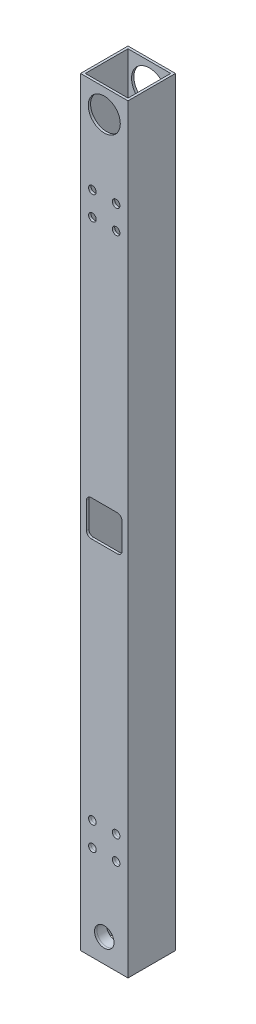
SolidWorks part; units mm, degrees
material "6061 合金"
ref_plane "前视基准面" through (0, 0, 0) normal (0, 0, 1) x (1, 0, 0)
ref_plane "上视基准面" through (0, 0, 0) normal (0, 1, 0) x (1, 0, 0)
ref_plane "右视基准面" through (0, 0, 0) normal (1, 0, 0) x (0, 0, -1)
sketch "草图1" plane through (0, 0, 0) normal (0, 1, 0) x (1, 0, 0)
  line L0 (1, 1) -> (1, 19)
  line L1 (0, 0) -> (20, 0)
  line L2 (0, 0) -> (0, 20)
  line L3 (0, 20) -> (20, 20)
  line L4 (20, 0) -> (20, 20)
  line L5 (1, 19) -> (19, 19)
  line L6 (19, 1) -> (19, 19)
  line L7 (1, 1) -> (19, 1)
  dimension "D1" = 20
  dimension "D2" = 1
extrude "凸台-拉伸1" add sketch "草图1" along normal blind 320
sketch "草图2" plane through (0, 0, -20) normal (0, 0, -1) x (-1, 0, 0)
  line L0 (-20, 160) -> (0, 160) construction
  line L1 (-20, 320) -> (-20, 0) construction
  line L3 (-5.0503, 155.0503) -> (-14.9497, 155.0503) construction
  line L4 (-5.0503, 155.0503) -> (-5.0503, 164.9497) construction
  line L5 (-5.0503, 164.9497) -> (-14.9497, 164.9497) construction
  line L6 (-14.9497, 155.0503) -> (-14.9497, 164.9497) construction
  line L7 (-5.0503, 155.0503) -> (-14.9497, 164.9497) construction
  line L8 (-5.0503, 164.9497) -> (-14.9497, 155.0503) construction
  line L9 (0, 320) -> (0, 0) construction
  circle A0 centre (-14.9497, 155.0503) radius 1.6
  circle A1 centre (-14.9497, 164.9497) radius 1.6
  circle A2 centre (-5.0503, 164.9497) radius 1.6
  circle A3 centre (-5.0503, 155.0503) radius 1.6
  point P4 (-10, 160)
  dimension "D2" = 3.2
  dimension "D1" = 14
extrude "切除-拉伸1" cut sketch "草图2" against normal through all
sketch "草图3" plane through (0, 0, 0) normal (0, 0, 1) x (1, 0, 0)
  line L0 (20, 160) -> (0, 160) construction
  line L5 (20, 320) -> (20, 0) construction
  line L6 (0, 320) -> (0, 0) construction
  line L8 (4.5, 167.5) -> (15.5, 167.5)
  line L9 (2.5, 165.5) -> (2.5, 154.5)
  line L10 (4.5, 152.5) -> (15.5, 152.5)
  line L11 (17.5, 165.5) -> (17.5, 154.5)
  line L12 (2.5, 167.5) -> (17.5, 152.5) construction
  line L13 (2.5, 152.5) -> (17.5, 167.5) construction
  arc A6 (15.5, 152.5) -> (17.5, 154.5) centre (15.5, 154.5) ccw
  arc A7 (2.5, 154.5) -> (4.5, 152.5) centre (4.5, 154.5) ccw
  arc A8 (4.5, 167.5) -> (2.5, 165.5) centre (4.5, 165.5) ccw
  arc A9 (15.5, 167.5) -> (17.5, 165.5) centre (15.5, 165.5) cw
  point P6 (10, 160)
  dimension "D2" = 2
  dimension "D1" = 15
extrude "切除-拉伸2" cut sketch "草图3" against normal up to next
sketch "草图4" plane through (0, 0, 0) normal (0, 0, 1) x (1, 0, 0)
  line L0 (20, 160) -> (0, 160) construction
  line L1 (20, 320) -> (20, 0) construction
  line L2 (0, 320) -> (0, 0) construction
  line L3 (20, 10) -> (0, 10) construction
  line L4 (20, 310) -> (0, 310) construction
  circle A0 centre (10, 10) radius 4.1
  circle A1 centre (10, 310) radius 6.75
  point P12 (10, 160)
  dimension "D1" = 8.2
  dimension "D4" = 13.5
  dimension "D2" = 150
  dimension "D3" = 150
extrude "切除-拉伸3" cut sketch "草图4" against normal through all
sketch "草图5" plane through (0, 0, -20) normal (0, 0, -1) x (-1, 0, 0)
  line L0 (-20, 160) -> (0, 160) construction
  line L1 (-20, 320) -> (-20, 0) construction
  line L2 (0, 320) -> (0, 0) construction
  circle A0 centre (-10, 10) radius 4.1 construction
  circle A1 centre (-10, 10) radius 4.1 construction
  circle A2 centre (-10, 10) radius 7.5
  circle A3 centre (-10, 310) radius 7.5
  dimension "D1" = 15
extrude "切除-拉伸4" cut sketch "草图5" against normal up to next and the other way through all
sketch "草图8" plane through (0, 0, -1) normal (0, 0, -1) x (-1, 0, 0)
  line L0 (-1, 0) -> (-19, 0) construction
  line L1 (-1.1, 0) -> (-18.9, 0)
  line L2 (-1.1, 0) -> (-1.1, 60)
  line L3 (-1.1, 60) -> (-18.9, 60)
  line L4 (-18.9, 0) -> (-18.9, 60)
  line L5 (-19, 320) -> (-19, 0) construction
  line L6 (-1, 320) -> (-1, 0) construction
  circle A0 centre (-10, 10) radius 4.1 construction
  circle A1 centre (-10, 10) radius 4.1
  dimension "D1" = 60
  dimension "D2" = 0.1
  dimension "D3" = 0.1
extrude "凸台-拉伸3" add sketch "草图8" along normal blind 4 separate body
sketch "草图9" plane through (0, 0, 0) normal (0, 0, 1) x (1, 0, 0)
  line L0 (20, 45) -> (0, 45) construction
  line L1 (5, 50) -> (15, 50) construction
  line L2 (5, 50) -> (5, 40) construction
  line L3 (5, 40) -> (15, 40) construction
  line L4 (15, 50) -> (15, 40) construction
  line L5 (5, 50) -> (15, 40) construction
  line L6 (5, 40) -> (15, 50) construction
  line L7 (20, 320) -> (20, 0) construction
  line L8 (0, 320) -> (0, 0) construction
  line L9 (0, 0) -> (20, 0) construction
  line L10 (20, 160) -> (0, 160) construction
  circle A0 centre (15, 40) radius 1.6
  circle A1 centre (5, 40) radius 1.6
  circle A2 centre (5, 50) radius 1.6
  circle A3 centre (15, 50) radius 1.6
  circle A4 centre (15, 280) radius 1.6
  circle A5 centre (5, 280) radius 1.6
  circle A6 centre (5, 270) radius 1.6
  circle A7 centre (15, 270) radius 1.6
  point P0 (10, 45)
  dimension "D2" = 3.2
  dimension "D1" = 45
  dimension "D3" = 10
extrude "切除-拉伸5" cut sketch "草图9" against normal through all
sketch "草图10" plane through (0, 0, -20) normal (0, 0, -1) x (-1, 0, 0)
  line L0 (0, 160) -> (-20, 160) construction
  line L1 (0, 320) -> (0, 0) construction
  line L2 (-20, 320) -> (-20, 0) construction
  circle A0 centre (-5, 50) radius 4
  circle A1 centre (-5, 40) radius 4
  circle A2 centre (-15, 50) radius 4
  circle A3 centre (-15, 40) radius 4
  circle A4 centre (-15, 280) radius 4
  circle A5 centre (-15, 270) radius 4
  circle A6 centre (-5, 280) radius 4
  circle A7 centre (-5, 270) radius 4
  dimension "D1" = 8
extrude "切除-拉伸6" cut sketch "草图10" against normal up to next (1 mm away)
